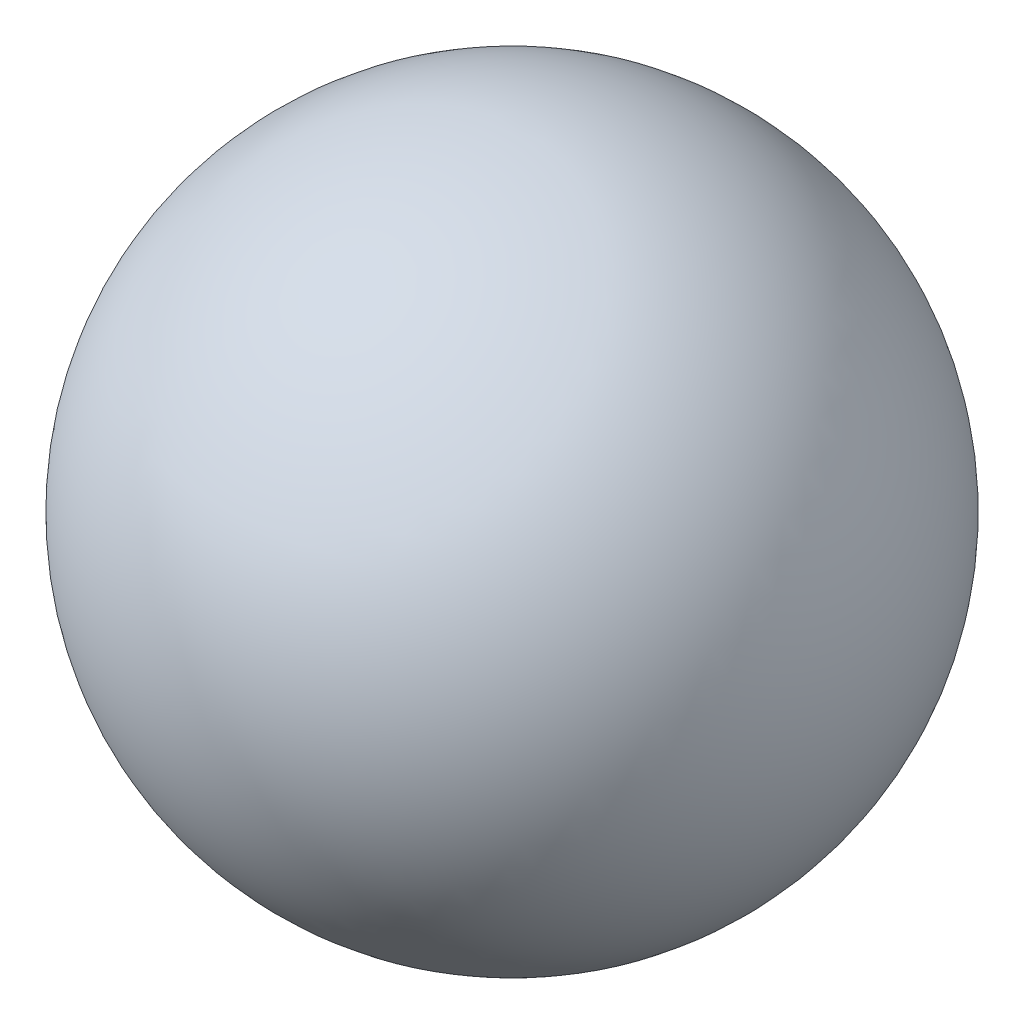
SolidWorks part; units mm, degrees
ref_plane "Front Plane" through (0, 0, 0) normal (0, 0, 1) x (1, 0, 0)
ref_plane "Top Plane" through (0, 0, 0) normal (0, 1, 0) x (1, 0, 0)
ref_plane "Right Plane" through (0, 0, 0) normal (1, 0, 0) x (0, 0, -1)
sketch "Sketch1" plane through (0, 0, 0) normal (0, 0, 1) x (1, 0, 0)
  line L0 (0, 8.5) -> (0, -8.5)
  arc A0 (0, -8.5) -> (0, 8.5) centre (0, 0) ccw
  point P4 (0, 0)
  dimension "D1" = 8.5
revolve "Revolve1" add sketch "Sketch1" angle 360 about L0
